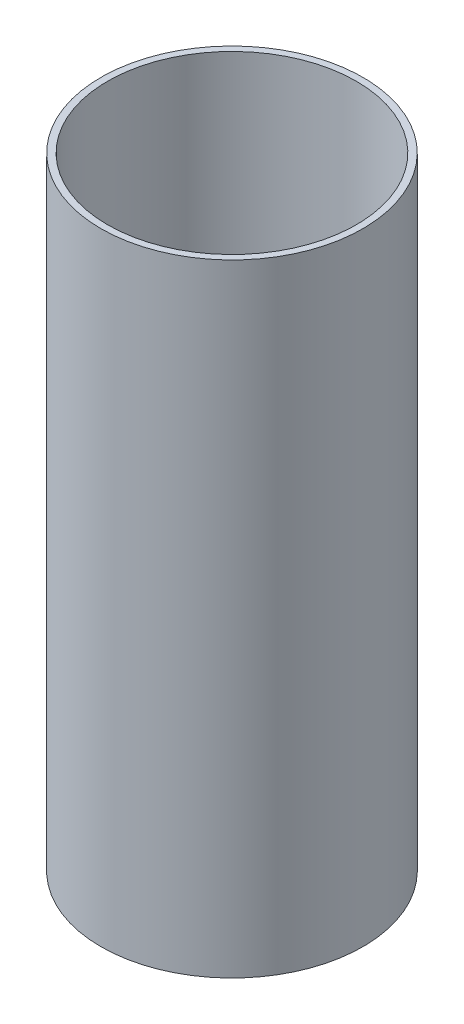
SolidWorks part; units mm, degrees
material "PVC Rigid"
ref_plane "Front Plane" through (0, 0, 0) normal (0, 0, 1) x (1, 0, 0)
ref_plane "Top Plane" through (0, 0, 0) normal (0, 1, 0) x (1, 0, 0)
ref_plane "Right Plane" through (0, 0, 0) normal (1, 0, 0) x (0, 0, -1)
sketch "Sketch1" plane through (0, 0, 0) normal (0, 1, 0) x (1, 0, 0)
  circle A0 centre (0, 0) radius 93.6625
  circle A1 centre (0, 0) radius 88.9
  dimension "D1" = 187.325
  dimension "D2" = 177.8
extrude "Boss-Extrude1" add sketch "Sketch1" along normal mid plane 444.5
ref_plane "Plane1" through (-93.6625, 0, 0) normal (-1, 0, 0) x (0, 0, 1)
sketch "Sketch3" plane through (-93.6625, 0, 0) normal (-1, 0, 0) x (0, 0, 1)
  line L0 (0, -103.0288) -> (0, 103.0288) construction
  line L1 (-88.9, -222.25) -> (88.9, -222.25) construction
  circle A0 centre (0, -215.9) radius 1.4351
  dimension "D1" = 2.8702
  dimension "D2" = 6.35
extrude "Cut-Extrude1" [suppressed] cut sketch "Sketch3" against normal blind 21.59
pattern_circular "CirPattern1" [suppressed] count 12 over 360
sketch "Sketch4" plane through (-93.6625, 0, 0) normal (-1, 0, 0) x (0, 0, 1)
  line L0 (0, -103.0288) -> (0, 103.0288) construction
  line L1 (93.6625, 222.25) -> (-93.6625, 222.25) construction
  circle A0 centre (0, 215.9) radius 1.4351
  dimension "D1" = 2.8702
  dimension "D2" = 6.35
extrude "Cut-Extrude2" [suppressed] cut sketch "Sketch4" against normal blind 34.798
pattern_circular "CirPattern2" [suppressed] count 3 over 360
sketch "Sketch9" [suppressed] plane through (-93.6625, 0, 0) normal (-1, 0, 0) x (0, 0, 1)
  line L0 (0, -103.0288) -> (0, 103.0288) construction
  circle A0 centre (0, 136.398) radius 1.4351
  circle A1 centre (0, 215.9) radius 1.4351 construction
  dimension "D1" = 79.502
  dimension "D2" = 2.8702
extrude "Cut-Extrude4" [suppressed] cut sketch "Sketch9" against normal blind 15.24
pattern_circular "CirPattern4" [suppressed] count 12 over 360
sketch "Sketch7" [suppressed] plane through (-93.6625, 0, 0) normal (-1, 0, 0) x (0, 0, 1)
  line L0 (0, -103.0288) -> (0, 103.0288) construction
  circle A0 centre (0, 19.05) radius 1.4351
  circle A1 centre (0, -98.552) radius 1.4351
  circle A4 centre (0, 136.398) radius 1.4351 construction
  circle A5 centre (0, -215.9) radius 1.4351 construction
  dimension "D1" = 117.348
  dimension "D2" = 117.348
  dimension "D3" = 2.8702
  dimension "D4" = 2.8702
extrude "Cut-Extrude3" [suppressed] cut sketch "Sketch7" against normal blind 15.24
pattern_circular "CirPattern3" [suppressed] count 3 over 360
